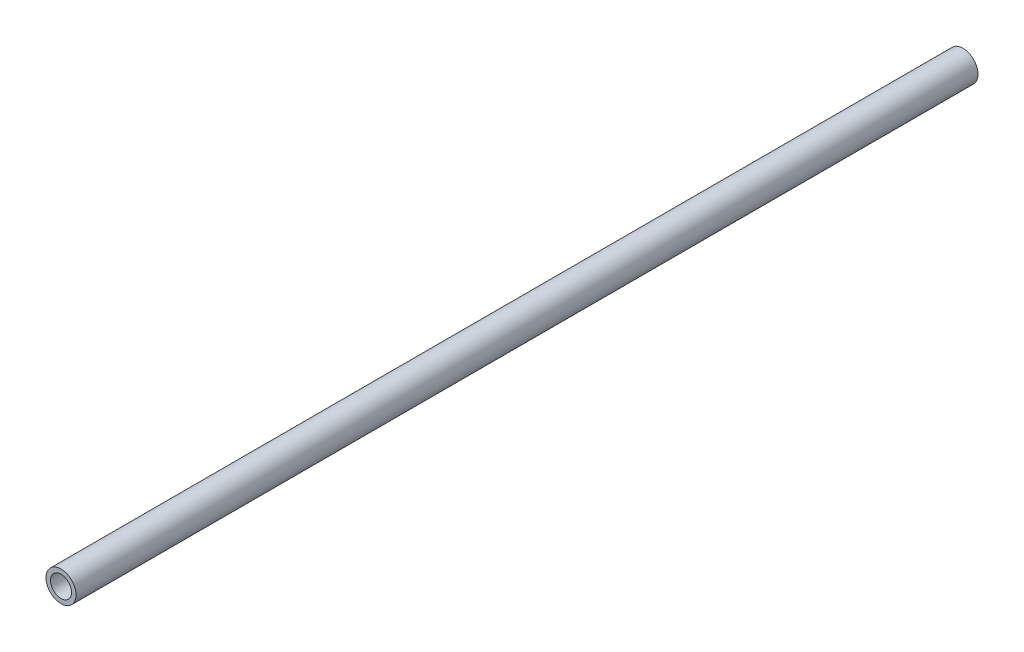
SolidWorks part; units mm, degrees
ref_plane "Front Plane" through (0, 0, 0) normal (0, 0, 1) x (1, 0, 0)
ref_plane "Top Plane" through (0, 0, 0) normal (0, 1, 0) x (1, 0, 0)
ref_plane "Right Plane" through (0, 0, 0) normal (1, 0, 0) x (0, 0, -1)
sketch "Sketch1" plane through (0, 0, 0) normal (0, 0, 1) x (1, 0, 0)
  circle A0 centre (0, 0) radius 17.5
  circle A1 centre (0, 0) radius 25
  dimension "D1" = 50
  dimension "D2" = 35
extrude "Boss-Extrude1" add sketch "Sketch1" along normal blind 1500
